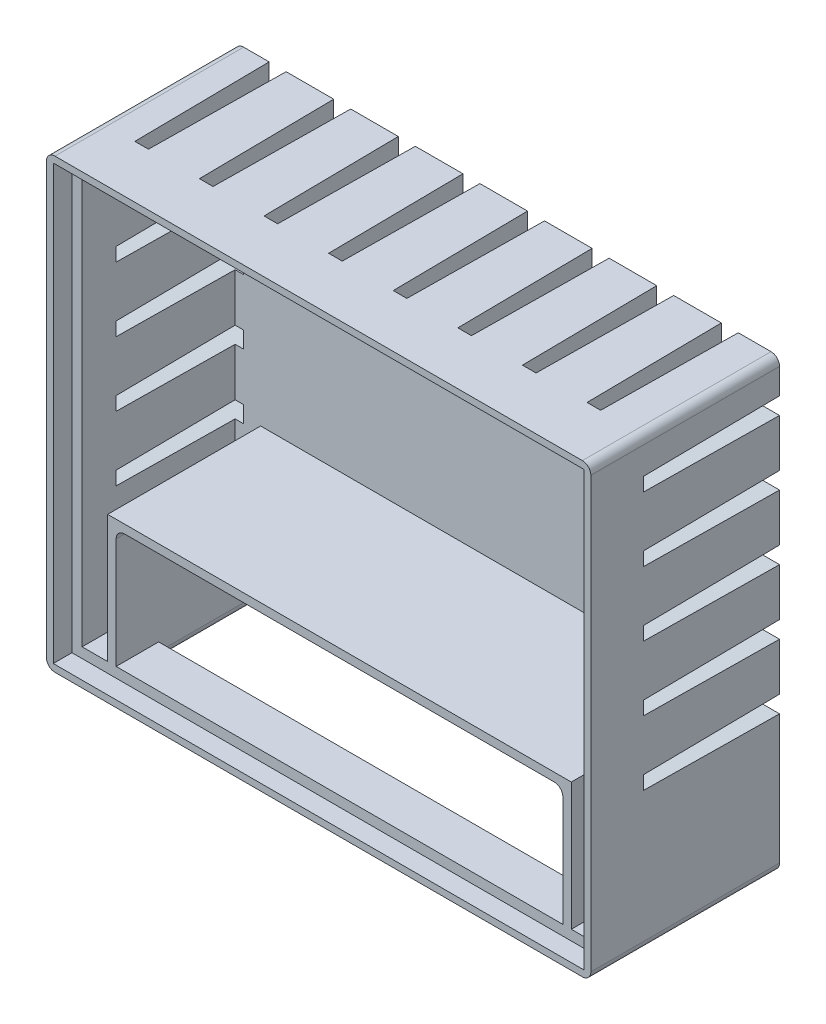
SolidWorks part; units mm, degrees
ref_plane "Front Plane" through (0, 0, 0) normal (0, 0, 1) x (1, 0, 0)
ref_plane "Top Plane" through (0, 0, 0) normal (0, 1, 0) x (1, 0, 0)
ref_plane "Right Plane" through (0, 0, 0) normal (1, 0, 0) x (0, 0, -1)
sketch "Sketch1" plane through (0, 0, 0) normal (0, 0, 1) x (1, 0, 0)
  line L0 (-2.5, 50.1) -> (61.55, 50.1)
  line L1 (0, 0) -> (59.05, 0) construction
  line L2 (0, 0) -> (0, 47.6) construction
  line L3 (0, 47.6) -> (59.05, 47.6) construction
  line L4 (59.05, 0) -> (59.05, 47.6) construction
  line L5 (61.55, -2.5) -> (61.55, 50.1)
  line L6 (-2.5, -2.5) -> (61.55, -2.5)
  line L7 (-2.5, -2.5) -> (-2.5, 50.1)
  dimension "D1" = 47.6
  dimension "D2" = 59.05
  dimension "D3" = 2.5
extrude "Boss-Extrude1" add sketch "Sketch1" along normal blind 2
sketch "Sketch2" plane through (0, 0, 2) normal (0, 0, 1) x (1, 0, 0)
  line L0 (59.55, 48.1) -> (-0.5, 48.1)
  line L1 (-0.5, 48.1) -> (-0.5, -0.5)
  line L2 (-0.5, -0.5) -> (59.55, -0.5)
  line L3 (59.55, -0.5) -> (59.55, 48.1)
  line L4 (-2.5, 50.1) -> (-2.5, -2.5)
  line L5 (-2.5, -2.5) -> (61.55, -2.5)
  line L6 (61.55, -2.5) -> (61.55, 50.1)
  line L7 (61.55, 50.1) -> (-2.5, 50.1)
  line L8 (-2.5, 50.1) -> (-2.5, -2.5)
  line L9 (-2.5, -2.5) -> (61.55, -2.5)
  line L10 (61.55, -2.5) -> (61.55, 50.1)
  line L11 (61.55, 50.1) -> (-2.5, 50.1)
  dimension "D1" = 0
  dimension "D2" = 2
extrude "Boss-Extrude2" add sketch "Sketch2" along normal blind 18
sketch "Sketch3" plane through (0, 0, 20) normal (0, 0, 1) x (1, 0, 0)
  line L0 (61.55, -2.5) -> (61.55, 50.1) construction
  line L1 (-2.5, -2.5) -> (61.55, -2.5) construction
  line L2 (-2.5, 50.1) -> (-2.5, -2.5) construction
  line L3 (61.55, 50.1) -> (-2.5, 50.1) construction
  line L4 (61.55, -2.5) -> (61.55, 50.1)
  line L5 (-2.5, -2.5) -> (61.55, -2.5)
  line L6 (-2.5, 50.1) -> (-2.5, -2.5)
  line L7 (61.55, 50.1) -> (-2.5, 50.1)
  line L8 (-1.7, 49.3) -> (-1.7, -1.7)
  line L9 (-1.7, -1.7) -> (60.75, -1.7)
  line L10 (60.75, -1.7) -> (60.75, 49.3)
  line L11 (60.75, 49.3) -> (-1.7, 49.3)
  dimension "D1" = 0.8
extrude "Boss-Extrude3" add sketch "Sketch3" along normal blind 2.2
ref_plane "Plane1" through (0, 23.8, 0) normal (0, 1, 0) x (1, 0, 0)
sketch "Sketch6" plane through (0, 0, 0) normal (0, 0, -1) x (-1, 0, 0)
  line L0 (2.5, -2.5) -> (-61.55, -2.5) construction
  line L1 (-3.5, -2.5) -> (-56.05, -2.5)
  line L2 (-3.5, -2.5) -> (-3.5, 13.5)
  line L3 (-3.5, 13.5) -> (-56.05, 13.5)
  line L4 (-56.05, -2.5) -> (-56.05, 13.5)
  line L5 (-61.55, -2.5) -> (-61.55, 50.1) construction
  line L6 (2.5, 50.1) -> (2.5, -2.5) construction
  dimension "D1" = 5.5
  dimension "D2" = 6
  dimension "D3" = 16
extrude "Cut-Extrude2" cut sketch "Sketch6" against normal blind 15
sketch "Sketch7" plane through (0, 0, 2) normal (0, 0, 1) x (1, 0, 0)
  line L0 (56.05, 13.5) -> (56.05, -0.5) construction
  line L1 (3.5, 13.5) -> (56.05, 13.5) construction
  line L2 (3.5, -0.5) -> (3.5, 13.5) construction
  line L3 (56.05, 13.5) -> (56.05, -0.5)
  line L4 (3.5, 13.5) -> (56.05, 13.5)
  line L5 (3.5, -0.5) -> (3.5, 13.5)
  line L6 (2.5, -0.5) -> (2.5, 14.5)
  line L7 (2.5, 14.5) -> (57.05, 14.5)
  line L8 (57.05, 14.5) -> (57.05, -0.5)
  line L9 (3.5, -0.5) -> (2.5, -0.5)
  line L10 (56.05, -0.5) -> (57.05, -0.5)
  dimension "D1" = 1
extrude "Boss-Extrude4" add sketch "Sketch7" along normal up to surface (18 mm away) up to face at (29.525, 23.8, 20)
sketch "Sketch8" plane through (0, 50.1, 0) normal (0, 1, 0) x (1, 0, 0)
  line L0 (1.5, 0) -> (3.5, 0)
  line L1 (61.55, 0) -> (-2.5, 0) construction
  line L2 (3.5, 0) -> (3.3, -16)
  line L3 (3.3, -16) -> (1.7, -16)
  line L4 (1.7, -16) -> (1.5, 0)
  line L5 (2.5, 0) -> (2.5, -16) construction
  line L6 (-2.5, -22.2) -> (-2.5, 0) construction
  dimension "D1" = 2
  dimension "D2" = 1.6
  dimension "D3" = 16
  dimension "D4" = 5
extrude "Cut-Extrude3" cut sketch "Sketch8" against normal blind 3
pattern_linear "LPattern1" count 8 spacing 7.6 along (1, 0, 0) of "Cut-Extrude3"
sketch "Sketch9" plane through (61.55, 0, 0) normal (1, 0, 0) x (0, 0, -1)
  line L0 (0, 46.1) -> (0, 44.1)
  line L1 (0, -2.5) -> (0, 50.1) construction
  line L2 (0, 44.1) -> (-16, 44.3)
  line L3 (-16, 44.3) -> (-16, 45.9)
  line L4 (-16, 45.9) -> (0, 46.1)
  line L5 (0, 45.1) -> (-16, 45.1) construction
  line L6 (-22.2, 50.1) -> (0, 50.1) construction
  dimension "D1" = 5
  dimension "D2" = 2
  dimension "D3" = 1.6
  dimension "D4" = 16
extrude "Cut-Extrude4" cut sketch "Sketch9" against normal blind 3
pattern_linear "LPattern2" count 5 spacing 7.6 along (0, -1, 0) of "Cut-Extrude4"
ref_plane "Plane2" through (29.525, 0, 0) normal (1, 0, 0) x (0, 0, -1)
mirror "Mirror1" about plane through (29.525, 0, 0) normal (1, 0, 0) of "LPattern2", "Cut-Extrude4"
fillet "Fillet1" radius 1 8 edges at (61.55, 50.1, 11.1) (61.55, -2.5, 11.1) (-2.5, 50.1, 11.1) (-2.5, -2.5, 11.1) (3.5, -2.5, 7.5) (3.5, 13.5, 10) (56.05, 13.5, 10) (56.05, -2.5, 7.5)
sketch "Sketch10" plane through (0, 0, 0) normal (0, 0, -1) x (-1, 0, 0)
  line L0 (-3.5, -1.5) -> (-3.5, 12.5) construction
  line L1 (-3.5, 15.5) -> (-56.05, 15.5)
  line L2 (-3.5, 15.5) -> (-3.5, 45.5)
  line L3 (-3.5, 45.5) -> (-56.05, 45.5)
  line L4 (-56.05, 15.5) -> (-56.05, 45.5)
  line L5 (-56.05, 12.5) -> (-56.05, -1.5) construction
  line L6 (-4.5, 13.5) -> (-55.05, 13.5) construction
  dimension "D1" = 30
  dimension "D2" = 2
extrude "Cut-Extrude5" cut sketch "Sketch10" against normal blind 0.2
fillet "Fillet2" radius 2 4 edges at (3.5, 45.5, 0.1) (56.05, 45.5, 0.1) (56.05, 15.5, 0.1) (3.5, 15.5, 0.1)
